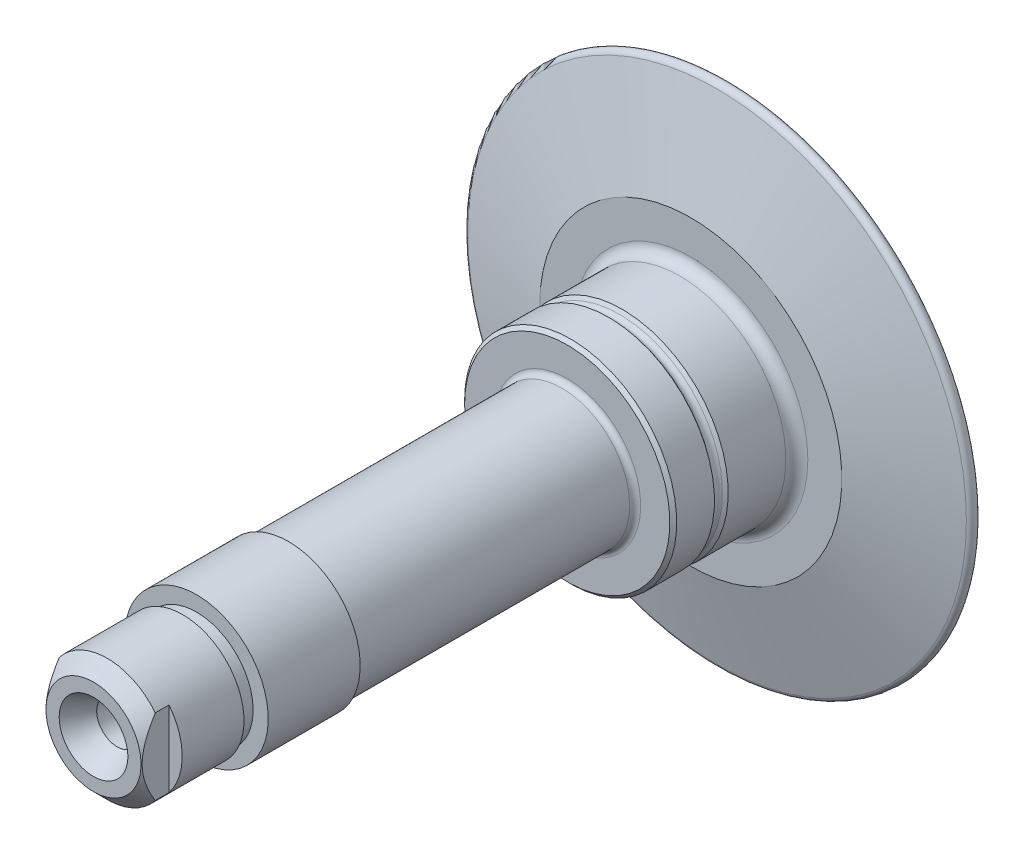
SolidWorks part; units mm, degrees
material "EN39B"
ref_plane "Front Plane" through (0, 0, 0) normal (0, 0, 1) x (1, 0, 0)
ref_plane "Top Plane" through (0, 0, 0) normal (0, 1, 0) x (1, 0, 0)
ref_plane "Right Plane" through (0, 0, 0) normal (1, 0, 0) x (0, 0, -1)
sketch "Sketch1" plane through (0, 0, 0) normal (1, 0, 0) x (0, 0, -1)
  line L0 (0, 0) -> (-65.6247, 0) construction
  line L1 (-14.25, 7.725) -> (-11.5, 7.725)
  line L2 (-5.5, 8.525) -> (-5.5, 11)
  line L3 (-5.5, 11) -> (-3.5829, 18.1546)
  line L4 (-14.25, 7.725) -> (-14.5, 7.475)
  line L5 (-14.5, 7.475) -> (-14.5, 5.35)
  line L6 (-14.9, 4.95) -> (-34.8, 4.95)
  line L7 (-34.8, 4.95) -> (-34.8, 5.225)
  line L8 (-34.8, 5.225) -> (-41.5, 5.225)
  line L9 (-41.5, 5.225) -> (-41.5, 4.125)
  line L10 (-42.5, 4.46) -> (-48, 4.46)
  line L11 (-48, 4.46) -> (-49, 3.46)
  line L12 (-49, 3.46) -> (-49, 2.5)
  line L13 (0, 0) -> (-43.2679, 0)
  line L14 (-42.5, 4.46) -> (-42.5, 4.125)
  line L15 (-42.5, 4.125) -> (-41.5, 4.125)
  line L16 (-49, 2.5) -> (-47.2679, 1.5)
  line L17 (-47.2679, 1.5) -> (-44.1692, 1.5)
  line L18 (-44.1692, 1.5) -> (-43.2679, 0)
  line L19 (-11, 9.6309) -> (-11, -0.9096) construction
  line L20 (-10.5, 7.725) -> (-6.3, 7.725)
  line L21 (-11.5, 7.725) -> (-11.3173, 7.487)
  line L22 (-10.5, 7.725) -> (-10.6827, 7.487)
  arc A0 (-2.8181, 18.1721) -> (0, 0) centre (-60, 0) cw
  arc A1 (-2.8181, 18.1721) -> (-3.5829, 18.1546) centre (-3.1979, 18.0514) ccw
  arc A2 (-6.3, 7.725) -> (-5.5, 8.525) centre (-6.3, 8.525) ccw
  arc A3 (-14.5, 5.35) -> (-14.9, 4.95) centre (-14.9, 5.35) cw
  arc A4 (-10.6827, 7.487) -> (-11.3173, 7.487) centre (-11, 7.7305) cw
  dimension "D12" = 49
  dimension "D13" = 75
  dimension "D14" = 36.9
  dimension "D15" = 60
  dimension "D17" = 0.8
  dimension "D18" = 0.4
  dimension "D28" = 0.4
  dimension "D29" = 75
  dimension "D1" = 15.45
  dimension "D2" = 22
  dimension "D3" = 0.25
  dimension "D4" = 45
  dimension "D5" = 9.9
  dimension "D6" = 10.45
  dimension "D7" = 8.92
  dimension "D8" = 7.5
  dimension "D9" = 36
  dimension "D10" = 6.7
  dimension "D11" = 9
  dimension "D16" = 1
  dimension "D19" = 1
  dimension "D20" = 8.25
  dimension "D21" = 3
  dimension "D22" = 59
  dimension "D23" = 4
  dimension "D24" = 5
  dimension "D25" = 30
  dimension "D26" = 3.5
  dimension "D27" = 1
revolve "Revolve1" add sketch "Sketch1" angle 360 about L0
cosmetic thread "Cosmetic Thread1"
sketch "Sketch2" plane through (0, 0, 49) normal (0, 0, 1) x (1, 0, 0)
  line L0 (0, 8.525) -> (0, -10.7875) construction
  line L1 (0, 0) -> (13.5036, 0) construction
  line L2 (3.5, 6.1191) -> (9.1409, 6.1191)
  line L3 (3.5, 6.1191) -> (3.5, -6.1191)
  line L4 (3.5, -6.1191) -> (9.1409, -6.1191)
  line L5 (9.1409, 6.1191) -> (9.1409, -6.1191)
  line L6 (-3.5, 6.1191) -> (-9.1409, 6.1191)
  line L7 (-9.1409, 6.1191) -> (-9.1409, -6.1191)
  line L8 (-3.5, -6.1191) -> (-9.1409, -6.1191)
  line L9 (-3.5, 6.1191) -> (-3.5, -6.1191)
  circle A0 centre (0, 0) radius 8.525 construction
  circle A1 centre (0, 0) radius 11 construction
  dimension "D1" = 18.2818
  dimension "D2" = 7
extrude "Cut-Extrude1" cut sketch "Sketch2" against normal blind 2
